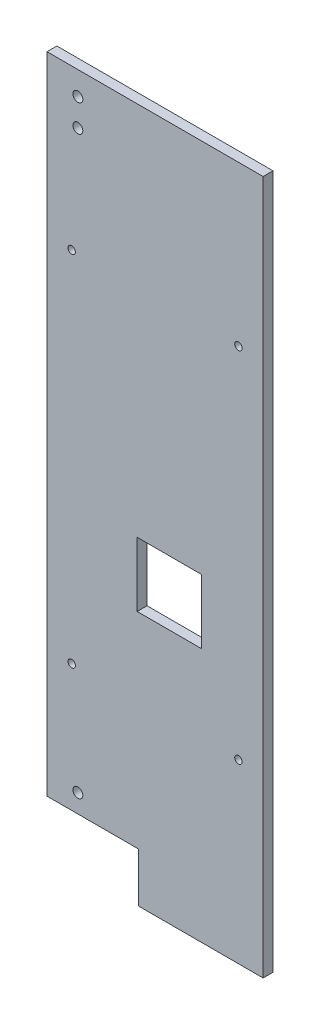
SolidWorks part; units mm, degrees
ref_plane "Plan de face" through (0, 0, 0) normal (0, 0, 1) x (1, 0, 0)
ref_plane "Plan de dessus" through (0, 0, 0) normal (0, 1, 0) x (1, 0, 0)
ref_plane "Plan de droite" through (0, 0, 0) normal (1, 0, 0) x (0, 0, -1)
sketch "Esquisse1" plane through (0, 0, 0) normal (0, 0, 1) x (1, 0, 0)
  line L0 (-20.5377, -30.3196) -> (-20.5377, -175.3196) construction
  line L1 (-30.5377, 34.1804) -> (56.9623, 34.1804)
  line L2 (-30.5377, 34.1804) -> (-30.5377, -226.8196)
  line L3 (6.4623, -246.8196) -> (56.9623, -246.8196)
  line L4 (56.9623, 34.1804) -> (56.9623, -246.8196)
  line L5 (46.9623, -30.3196) -> (46.9623, -175.3196) construction
  line L7 (-18.0377, 24.6804) -> (-18.0377, 13.6804) construction
  line L8 (5.9623, -117.8196) -> (31.9623, -117.8196)
  line L9 (5.9623, -117.8196) -> (5.9623, -143.8196)
  line L11 (5.9623, -143.8196) -> (31.9623, -143.8196)
  line L12 (31.9623, -117.8196) -> (31.9623, -143.8196)
  line L14 (-30.5377, -226.8196) -> (6.4623, -226.8196)
  line L15 (6.4623, -246.8196) -> (6.4623, -226.8196)
  circle A0 centre (-20.5377, -175.3196) radius 1.5
  circle A1 centre (-20.5377, -30.3196) radius 1.5
  circle A2 centre (46.9623, -30.3196) radius 1.5
  circle A3 centre (46.9623, -175.3196) radius 1.5
  circle A7 centre (-18.0377, -219.3196) radius 2
  circle A9 centre (-18.0377, 24.6804) radius 2
  circle A10 centre (-18.0377, 13.6804) radius 2
  dimension "D6" = 10
  dimension "D9" = 12.5
  dimension "D12" = 36.5
  dimension "D14" = 27.5
  dimension "D17" = 12.5
  dimension "D1" = 87.5
  dimension "D3" = 10
  dimension "D4" = 64.5
  dimension "D5" = 71.5
  dimension "D7" = 64.5
  dimension "D8" = 71.5
  dimension "D10" = 281
  dimension "D11" = 103
  dimension "D13" = 26
  dimension "D15" = 26
  dimension "D18" = 11
  dimension "D19" = 9.5
  dimension "D26" = 20
  dimension "D27" = 37
extrude "Extrusion1" add sketch "Esquisse1" along normal blind 4
